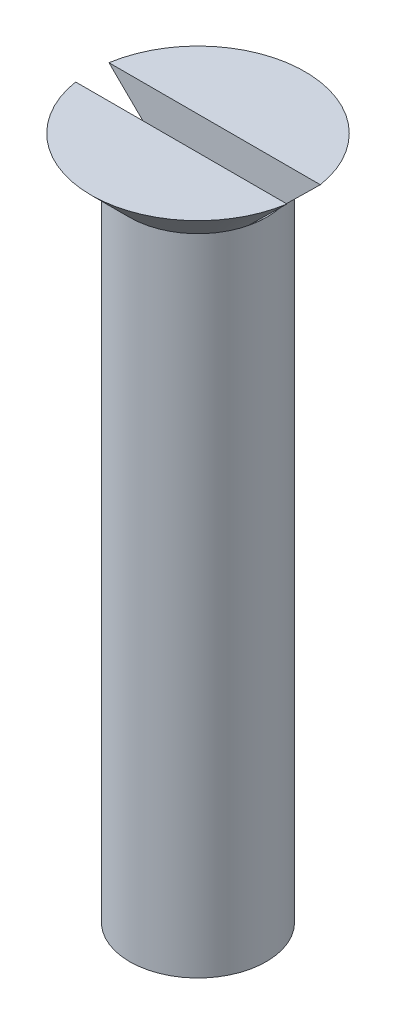
SolidWorks part; units mm, degrees
ref_plane "Front Plane" through (0, 0, 0) normal (0, 0, 1) x (1, 0, 0)
ref_plane "Top Plane" through (0, 0, 0) normal (0, 1, 0) x (1, 0, 0)
ref_plane "Right Plane" through (0, 0, 0) normal (1, 0, 0) x (0, 0, -1)
sketch "Sketch1" plane through (0, 0, 0) normal (0, 0, 1) x (1, 0, 0)
  line L0 (0, 13.2071) -> (-3.9142, 13.2071)
  line L1 (-3.9142, 13.2071) -> (-2.5, 11.7929)
  line L2 (-2.5, 11.7929) -> (-2.5, -11.7929)
  line L3 (-2.5, -11.7929) -> (0, -11.7929)
  line L4 (0, 14.9922) -> (0, -23.715) construction
  line L5 (0, 13.2071) -> (0, -11.7929)
  point P8 (0, 0)
  point P9 (-2.5, 0)
  dimension "D1" = 25
  dimension "D2" = 5
  dimension "D3" = 2
  dimension "D4" = 45
revolve "Revolve1" add sketch "Sketch1" angle 360 about L4
sketch "Sketch2" plane through (0, 0, 0) normal (1, 0, 0) x (0, 0, -1)
  line L0 (3.9142, 13.2071) -> (-3.9142, 13.2071) construction
  line L1 (0.6099, 11.8396) -> (-0.6099, 11.8396)
  line L2 (0.6099, 11.8396) -> (0.6099, 14.5746)
  line L3 (0.6099, 14.5746) -> (-0.6099, 14.5746)
  line L4 (-0.6099, 11.8396) -> (-0.6099, 14.5746)
  line L5 (0.6099, 11.8396) -> (-0.6099, 14.5746) construction
  line L6 (0.6099, 14.5746) -> (-0.6099, 11.8396) construction
  point P0 (0, 13.2071)
extrude "Cut-Extrude1" cut sketch "Sketch2" against normal through all both and the other way through all
